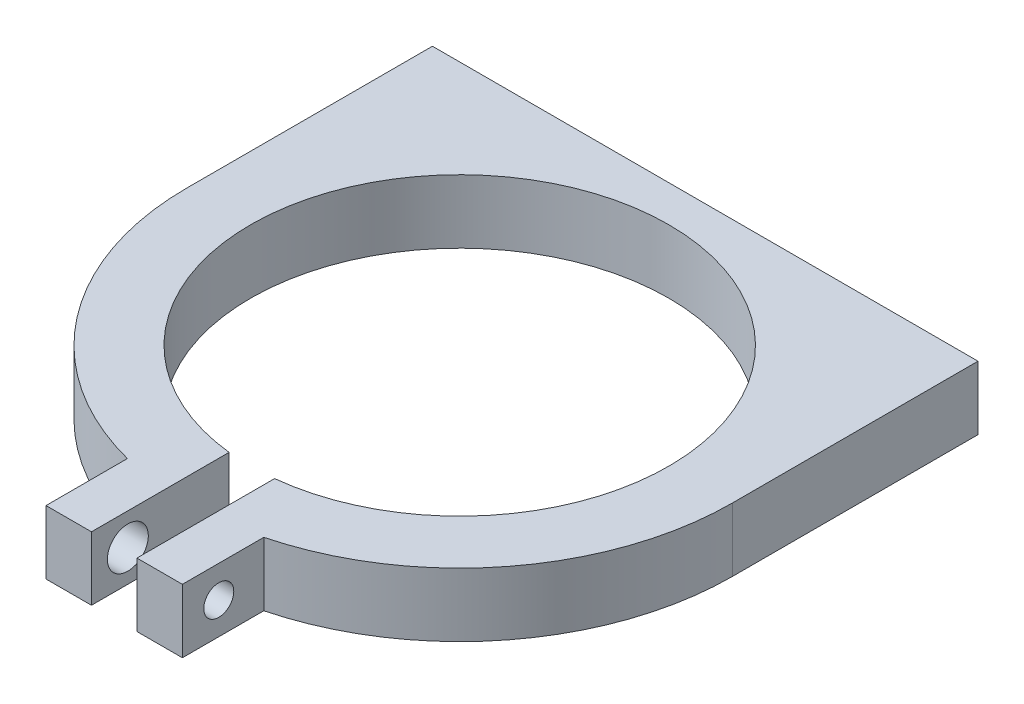
SolidWorks part; units mm, degrees
material "6061 Alloy"
ref_plane "Front Plane" through (0, 0, 0) normal (0, 0, 1) x (1, 0, 0)
ref_plane "Top Plane" through (0, 0, 0) normal (0, 1, 0) x (1, 0, 0)
ref_plane "Right Plane" through (0, 0, 0) normal (1, 0, 0) x (0, 0, -1)
sketch "Sketch1" plane through (0, 0, 0) normal (0, 1, 0) x (1, 0, 0)
  line L0 (-30, 0) -> (-30, 27)
  line L1 (-30, 27) -> (30, 27)
  line L2 (30, 27) -> (30, 0)
  line L3 (-2.5, -22.8637) -> (-2.5, -38)
  line L6 (-2.5, -38) -> (-7.5, -38)
  line L7 (-7.5, -38) -> (-7.5, -29.0474)
  line L8 (2.5, -22.8637) -> (2.5, -38)
  line L9 (2.5, -38) -> (7.5, -38)
  line L10 (7.5, -38) -> (7.5, -29.0474)
  arc A0 (-30, 0) -> (-7.5, -29.0474) centre (0, 0) ccw
  arc A1 (2.5, -22.8637) -> (-2.5, -22.8637) centre (0, 0) ccw
  arc A2 (7.5, -29.0474) -> (30, 0) centre (0, 0) ccw
  dimension "D1" = 30
  dimension "D3" = 46
  dimension "D2" = 27
  dimension "D4" = 65
  dimension "D5" = 2.5
  dimension "D6" = 5
extrude "Boss-Extrude1" add sketch "Sketch1" along normal mid plane 7
hole_wizard "M4 Tapped Hole2" positions "3DSketch1" profile "Sketch3" tap size "M4" standard "ISO"
sketch3d "3DSketch1"
  line L1 (-30, 0, -27) -> (30, 0, -27) construction
  line L2 (-30, 3.5, -27) -> (-30, -3.5, -27) construction
  line L3 (30, 3.5, -27) -> (30, -3.5, -27) construction
  point P0 (-24.75, 0, -27)
  point P1 (24.75, 0, -27)
  point P23 (0, 0, -27)
  dimension "D1" = 24.75
  dimension "D2" = 49.5
sketch "Sketch3" plane through (-24.75, 0, -27) normal (1, 0, 0) x (0, 1, 0)
  line L0 (0, 0) -> (0, 10)
  line L1 (0, 10) -> (1.65, 9.0086)
  line L2 (1.65, 9.0086) -> (1.65, 0)
  line L5 (1.65, 0) -> (0, 0)
  line L10 (0, 10) -> (-1.65, 9.0086) construction
  line L11 (0, -6.35) -> (0, 107.95) construction
  dimension "Tap Drill Dia." = 3.3
  dimension "Tap Drill Depth" = 10
  dimension "Drill Angle" = 118
cosmetic thread "Hole Thread1" parameters "D1"=8, "D2"=4
cosmetic thread "Hole Thread2" parameters "D1"=8, "D2"=4
sketch "Sketch4" plane through (-7.5, 0, 0) normal (-1, 0, 0) x (0, 0, 1)
  line L0 (38, 3.5) -> (38, -3.5) construction
  circle A0 centre (34, 0) radius 2.25
  point P5 (38, 0)
  dimension "D1" = 4.5
  dimension "D2" = 4
extrude "Cut-Extrude1" cut sketch "Sketch4" against normal up to next
sketch "Sketch5" plane through (7.5, 0, 0) normal (1, 0, 0) x (0, 0, -1)
  point P0 (-34, 0)
hole_wizard "M4 Tapped Hole1" positions "3DSketch2" profile "Sketch6" tap size "M4" standard "ISO"
sketch3d "3DSketch2"
  point P0 (7.5, 0, 34)
sketch "Sketch6" plane through (7.5, 0, 34) normal (0, 1, 0) x (0, 0, -1)
  line L0 (0, 0) -> (0, 10.1)
  line L1 (0, 10.1) -> (1.65, 9.1086)
  line L2 (1.65, 9.1086) -> (1.65, 0)
  line L5 (1.65, 0) -> (0, 0)
  line L10 (0, 10.1) -> (-1.65, 9.1086) construction
  line L11 (0, -6.35) -> (0, 107.95) construction
  dimension "Tap Drill Dia." = 3.3
  dimension "Tap Drill Depth" = 10.1
  dimension "Drill Angle" = 118
cosmetic thread "Hole Thread3" parameters "D1"=5, "D2"=4
